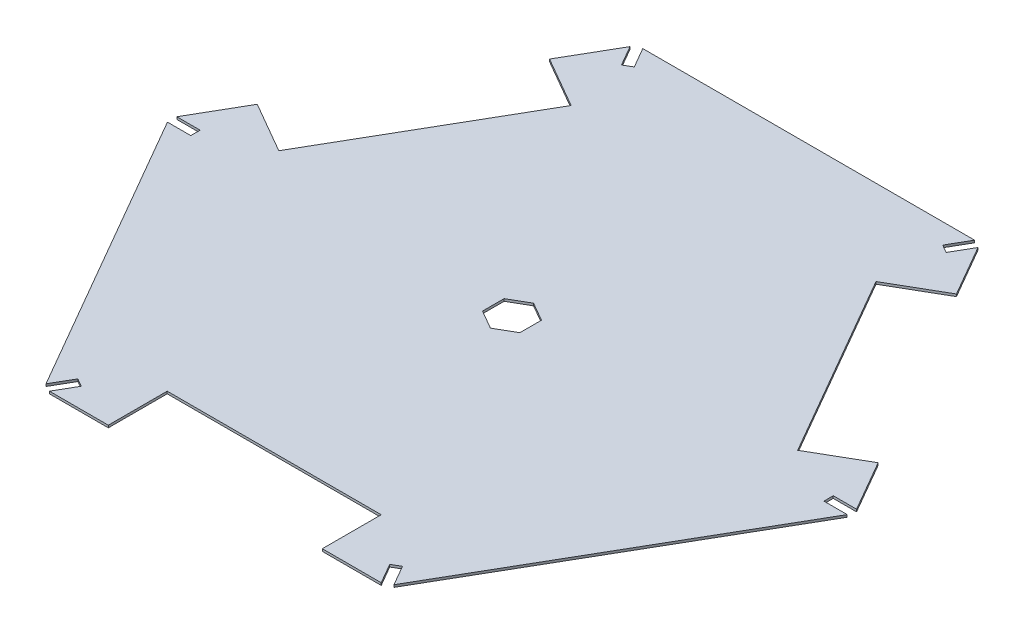
SolidWorks part; units mm, degrees
material "6061 Alloy"
ref_plane "Front Plane" through (0, 0, 0) normal (0, 0, 1) x (1, 0, 0)
ref_plane "Top Plane" through (0, 0, 0) normal (0, 1, 0) x (1, 0, 0)
ref_plane "Right Plane" through (0, 0, 0) normal (1, 0, 0) x (0, 0, -1)
sketch "Sketch1" plane through (0, 0, 0) normal (0, 1, 0) x (1, 0, 0)
  line L0 (157.3069, 5.3405) -> (44.6393, -189.8056)
  line L1 (44.6393, 206.8366) -> (157.3069, 11.6905)
  line L2 (157.3069, 11.6905) -> (44.6393, 206.8366)
  line L3 (39.14, 210.0116) -> (-186.1953, 210.0116)
  line L4 (-191.6946, 206.8366) -> (-304.3622, 11.6905)
  line L5 (-304.3622, 5.3405) -> (-191.6946, -189.8056)
  line L6 (-186.1953, -192.9806) -> (39.14, -192.9806)
  line L7 (44.6393, -189.8056) -> (157.3069, 5.3405)
  line L13 (-183.7773, -176.0925) -> (-178.278, -179.2675)
  line L15 (141.4723, 5.3405) -> (141.4723, 11.6905)
  line L16 (36.722, 193.1234) -> (31.2227, 196.2984)
  line L18 (-178.278, 196.2984) -> (-183.7773, 193.1234)
  line L20 (-288.5277, 11.6905) -> (-288.5277, 5.3405)
  line L21 (157.3069, 11.6905) -> (141.4723, 11.6905)
  line L23 (141.4723, 5.3405) -> (141.4723, 11.6905)
  line L24 (157.3069, 5.3405) -> (141.4723, 5.3405)
  line L25 (39.14, 210.0116) -> (31.2227, 196.2984)
  line L27 (36.722, 193.1234) -> (31.2227, 196.2984)
  line L28 (44.6393, 206.8366) -> (36.722, 193.1234)
  line L29 (-178.278, 196.2984) -> (-183.7773, 193.1234)
  line L30 (-191.6946, 206.8366) -> (-183.7773, 193.1234)
  line L31 (-186.1953, 210.0116) -> (-178.278, 196.2984)
  line L32 (-288.5277, 11.6905) -> (-288.5277, 5.3405)
  line L33 (-304.3622, 5.3405) -> (-288.5277, 5.3405)
  line L34 (-304.3622, 11.6905) -> (-288.5277, 11.6905)
  line L35 (-186.1953, -192.9806) -> (-178.278, -179.2675)
  line L36 (-183.7773, -176.0925) -> (-178.278, -179.2675)
  line L37 (-191.6946, -189.8056) -> (-183.7773, -176.0925)
  line L38 (44.6393, -189.8056) -> (36.722, -176.0925)
  line L39 (31.2227, -179.2675) -> (36.722, -176.0925)
  line L40 (39.14, -192.9806) -> (31.2227, -179.2675)
  line L41 (-86.2277, 1.1831) -> (-73.5277, -6.1492)
  line L42 (-73.5277, -6.1492) -> (-60.8277, 1.1831)
  line L43 (-60.8277, 1.1831) -> (-60.8277, 15.8478)
  line L44 (-60.8277, 15.8478) -> (-73.5277, 23.1802)
  line L45 (-73.5277, 23.1802) -> (-86.2277, 15.8478)
  line L46 (-86.2277, 15.8478) -> (-86.2277, 1.1831)
  circle A1 centre (-73.5277, 8.5155) radius 201.4961 construction
extrude "Boss-Extrude1" add sketch "Sketch1" along normal blind 1.5875 contours L6 L40 L39 L38 L0 L24 L15 L21 L1 L28 L16 L25 L3 L31 L18 L30 L4 L34 L20 L33 L5 L37 L13 L35 L46 L45 L44 L43 L42 L41
sketch "Sketch2" plane through (0, 1.5875, 0) normal (0, 1, 0) x (1, 0, 0)
  line L1 (-186.1953, -192.9806) -> (39.14, -192.9806) construction
  line L2 (-0.86, -192.9806) -> (-0.86, -152.9806)
  line L4 (-146.1953, -192.9806) -> (-146.1953, -152.9806)
  line L5 (-0.86, -152.9806) -> (-146.1953, -152.9806)
  line L6 (-0.86, -192.9806) -> (-146.1953, -192.9806)
  line L8 (137.3069, 46.3315) -> (64.6393, 172.1956)
  line L9 (102.6659, 26.3315) -> (29.9982, 152.1956)
  line L10 (64.6393, 172.1956) -> (29.9982, 152.1956)
  line L11 (137.3069, 46.3315) -> (102.6659, 26.3315)
  line L13 (-211.6946, 172.1956) -> (-284.3622, 46.3315)
  line L14 (-177.0536, 152.1956) -> (-249.7212, 26.3315)
  line L15 (-284.3622, 46.3315) -> (-249.7212, 26.3315)
  line L16 (-211.6946, 172.1956) -> (-177.0536, 152.1956)
extrude "Cut-Extrude1" cut sketch "Sketch2" against normal up to surface (1.5875 mm away) up to face at (-73.5277, 0, -8.5155)
sketch "Sketch3" plane through (0, 1.5875, 0) normal (0, 1, 0) x (1, 0, 0)
  line L36 (-146.1953, -192.9806) -> (-146.1953, -152.9806)
  line L37 (-146.1953, -152.9806) -> (-0.86, -152.9806)
  line L38 (-0.86, -152.9806) -> (-0.86, -192.9806)
  line L39 (-0.86, -192.9806) -> (39.14, -192.9806)
  line L40 (39.14, -192.9806) -> (31.2227, -179.2675)
  line L41 (31.2227, -179.2675) -> (36.722, -176.0925)
  line L42 (36.722, -176.0925) -> (44.6393, -189.8056)
  line L43 (44.6393, -189.8056) -> (157.3069, 5.3405)
  line L44 (157.3069, 5.3405) -> (141.4723, 5.3405)
  line L45 (141.4723, 5.3405) -> (141.4723, 11.6905)
  line L46 (141.4723, 11.6905) -> (157.3069, 11.6905)
  line L47 (157.3069, 11.6905) -> (137.3069, 46.3315)
  line L48 (137.3069, 46.3315) -> (102.6659, 26.3315)
  line L49 (102.6659, 26.3315) -> (29.9982, 152.1956)
  line L50 (29.9982, 152.1956) -> (64.6393, 172.1956)
  line L51 (64.6393, 172.1956) -> (44.6393, 206.8366)
  line L52 (44.6393, 206.8366) -> (36.722, 193.1234)
  line L53 (36.722, 193.1234) -> (31.2227, 196.2984)
  line L54 (31.2227, 196.2984) -> (39.14, 210.0116)
  line L55 (39.14, 210.0116) -> (-186.1953, 210.0116)
  line L56 (-186.1953, 210.0116) -> (-178.278, 196.2984)
  line L57 (-178.278, 196.2984) -> (-183.7773, 193.1234)
  line L58 (-183.7773, 193.1234) -> (-191.6946, 206.8366)
  line L59 (-191.6946, 206.8366) -> (-211.6946, 172.1956)
  line L60 (-211.6946, 172.1956) -> (-177.0536, 152.1956)
  line L61 (-177.0536, 152.1956) -> (-249.7212, 26.3315)
  line L62 (-249.7212, 26.3315) -> (-284.3622, 46.3315)
  line L63 (-284.3622, 46.3315) -> (-304.3622, 11.6905)
  line L64 (-304.3622, 11.6905) -> (-288.5277, 11.6905)
  line L65 (-288.5277, 11.6905) -> (-288.5277, 5.3405)
  line L66 (-288.5277, 5.3405) -> (-304.3622, 5.3405)
  line L67 (-304.3622, 5.3405) -> (-191.6946, -189.8056)
  line L68 (-191.6946, -189.8056) -> (-183.7773, -176.0925)
  line L69 (-183.7773, -176.0925) -> (-178.278, -179.2675)
  line L70 (-178.278, -179.2675) -> (-186.1953, -192.9806)
  line L71 (-186.1953, -192.9806) -> (-146.1953, -192.9806)
  line L72 (-146.1953, -192.9806) -> (-146.1953, -152.9806)
  line L73 (-146.1953, -152.9806) -> (-0.86, -152.9806)
  line L74 (-0.86, -152.9806) -> (-0.86, -192.9806)
  line L75 (-0.86, -192.9806) -> (39.14, -192.9806)
  line L76 (39.14, -192.9806) -> (31.2227, -179.2675)
  line L77 (31.2227, -179.2675) -> (36.722, -176.0925)
  line L78 (36.722, -176.0925) -> (44.6393, -189.8056)
  line L79 (44.6393, -189.8056) -> (157.3069, 5.3405)
  line L80 (157.3069, 5.3405) -> (141.4723, 5.3405)
  line L81 (141.4723, 5.3405) -> (141.4723, 11.6905)
  line L82 (141.4723, 11.6905) -> (157.3069, 11.6905)
  line L83 (157.3069, 11.6905) -> (137.3069, 46.3315)
  line L84 (137.3069, 46.3315) -> (102.6659, 26.3315)
  line L85 (102.6659, 26.3315) -> (29.9982, 152.1956)
  line L86 (29.9982, 152.1956) -> (64.6393, 172.1956)
  line L87 (64.6393, 172.1956) -> (44.6393, 206.8366)
  line L88 (44.6393, 206.8366) -> (36.722, 193.1234)
  line L89 (36.722, 193.1234) -> (31.2227, 196.2984)
  line L90 (31.2227, 196.2984) -> (39.14, 210.0116)
  line L91 (39.14, 210.0116) -> (-186.1953, 210.0116)
  line L92 (-186.1953, 210.0116) -> (-178.278, 196.2984)
  line L93 (-178.278, 196.2984) -> (-183.7773, 193.1234)
  line L94 (-183.7773, 193.1234) -> (-191.6946, 206.8366)
  line L95 (-191.6946, 206.8366) -> (-211.6946, 172.1956)
  line L96 (-211.6946, 172.1956) -> (-177.0536, 152.1956)
  line L97 (-177.0536, 152.1956) -> (-249.7212, 26.3315)
  line L98 (-249.7212, 26.3315) -> (-284.3622, 46.3315)
  line L99 (-284.3622, 46.3315) -> (-304.3622, 11.6905)
  line L100 (-304.3622, 11.6905) -> (-288.5277, 11.6905)
  line L101 (-288.5277, 11.6905) -> (-288.5277, 5.3405)
  line L102 (-288.5277, 5.3405) -> (-304.3622, 5.3405)
  line L103 (-304.3622, 5.3405) -> (-191.6946, -189.8056)
  line L104 (-191.6946, -189.8056) -> (-183.7773, -176.0925)
  line L105 (-183.7773, -176.0925) -> (-178.278, -179.2675)
  line L106 (-178.278, -179.2675) -> (-186.1953, -192.9806)
  line L107 (-186.1953, -192.9806) -> (-146.1953, -192.9806)
  dimension "D1" = 0
